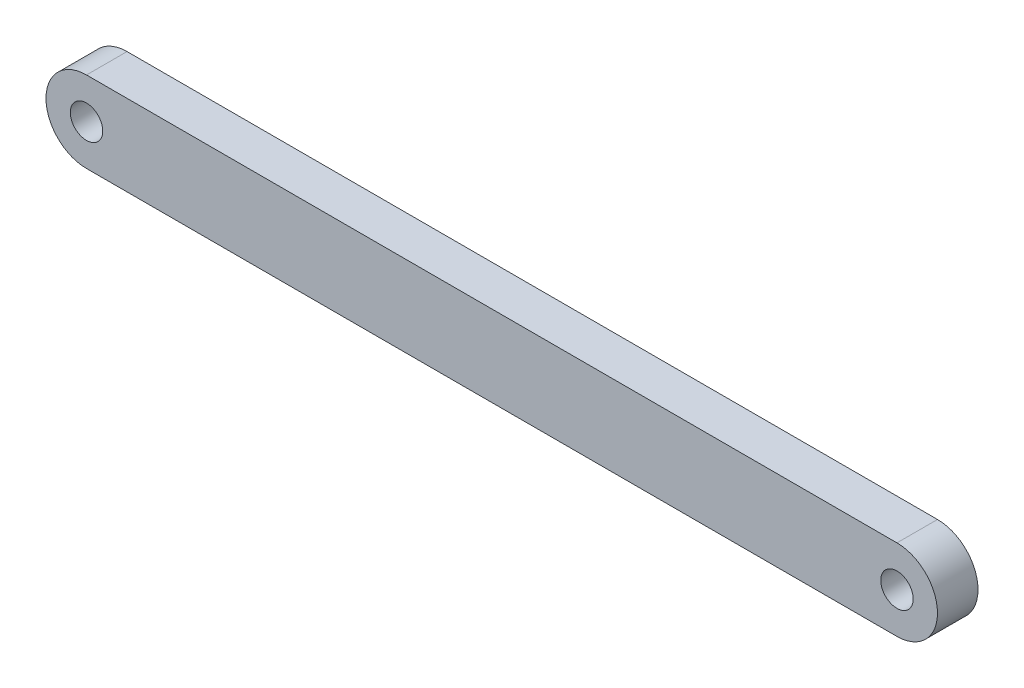
SolidWorks part; units mm, degrees
material "AISI 316 Stainless Steel Sheet (SS)"
ref_plane "Front Plane" through (0, 0, 0) normal (0, 0, 1) x (1, 0, 0)
ref_plane "Top Plane" through (0, 0, 0) normal (0, 1, 0) x (1, 0, 0)
ref_plane "Right Plane" through (0, 0, 0) normal (1, 0, 0) x (0, 0, -1)
sketch "Sketch1" plane through (0, 0, 0) normal (0, 0, 1) x (1, 0, 0)
  line L0 (-100, 0) -> (100, 0) construction
  line L1 (-100, 10) -> (100, 10)
  line L2 (-100, -10) -> (100, -10)
  arc A0 (-100, 10) -> (-100, -10) centre (-100, 0) ccw
  arc A1 (100, -10) -> (100, 10) centre (100, 0) ccw
  point P2 (0, 0)
  dimension "D1" = 20
  dimension "D2" = 200
extrude "Boss-Extrude1" add sketch "Sketch1" along normal mid plane 10
hole_wizard "Ø8.0mm Dowel Hole1" positions "Sketch2" profile "Sketch3" hole size "Ø8.0" standard "ISO" end condition through all
sketch "Sketch2" plane through (0, 0, 5) normal (0, 0, 1) x (1, 0, 0)
  point P0 (-100, 0)
  point P3 (100, 0)
sketch "Sketch3" plane through (-100, 0, 5) normal (1, 0, 0) x (0, -1, 0)
  line L0 (0, 0) -> (0, 10)
  line L1 (0, 10) -> (4, 10)
  line L2 (4, 10) -> (4, 0)
  line L5 (4, 0) -> (0, 0)
  line L11 (0, -6.35) -> (0, 107.95) construction
  dimension "Thru Hole Dia." = 8
  dimension "Thru Hole Depth" = 10
ref_point "Point1"
ref_point "Point2"
